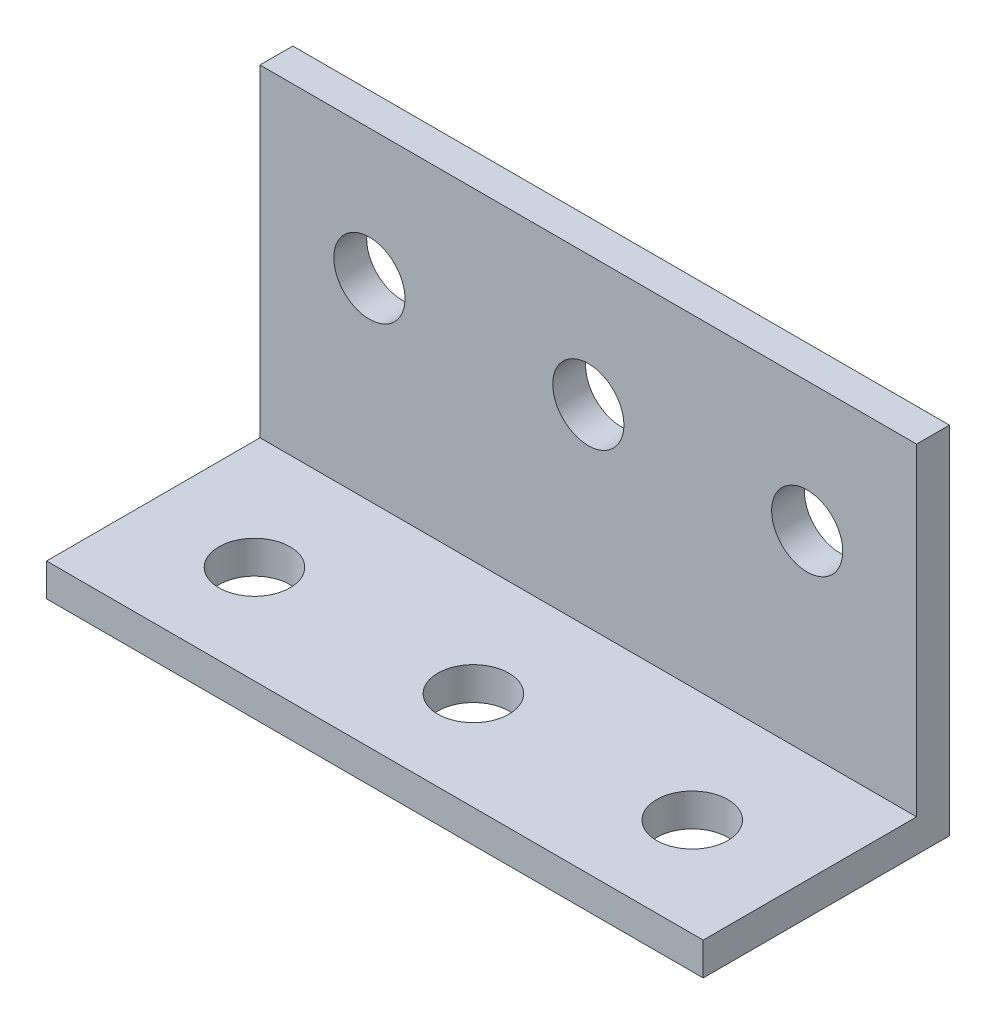
SolidWorks part; units mm, degrees
ref_plane "前视基准面" through (0, 0, 0) normal (0, 0, 1) x (1, 0, 0)
ref_plane "上视基准面" through (0, 0, 0) normal (0, 1, 0) x (1, 0, 0)
ref_plane "右视基准面" through (0, 0, 0) normal (1, 0, 0) x (0, 0, -1)
sketch "草图1" plane through (0, 0, 0) normal (0, 0, 1) x (1, 0, 0)
  line L1 (0, 0) -> (240, 0)
  line L2 (0, 0) -> (0, 130)
  line L3 (0, 130) -> (240, 130)
  line L4 (240, 0) -> (240, 130)
  dimension "D1" = 240
  dimension "D2" = 130
extrude "凸台-拉伸1" add sketch "草图1" along normal blind 90
sketch "草图2" plane through (0, 0, 0) normal (-1, 0, 0) x (0, 0, 1)
  line L0 (0, 130) -> (0, 0) construction
  line L1 (90, 130) -> (12, 130)
  line L2 (90, 130) -> (90, 12)
  line L3 (90, 12) -> (12, 12)
  line L4 (12, 130) -> (12, 12)
  line L5 (90, 0) -> (0, 0) construction
  dimension "D1" = 12
  dimension "D2" = 12
extrude "切除-拉伸1" cut sketch "草图2" against normal through all
sketch "草图3" plane through (0, 0, 0) normal (0, 0, -1) x (-1, 0, 0)
  line L0 (0, 0) -> (-240, 0) construction
  line L1 (-240, 0) -> (-240, 130) construction
  circle A0 centre (-200, 82.5) radius 13
  dimension "D1" = 26
  dimension "D2" = 82.5
  dimension "D3" = 40
extrude "切除-拉伸2" cut sketch "草图3" against normal through all
pattern_linear "阵列(线性)1" count 3 spacing 80 along (-1, 0, 0) of "切除-拉伸2"
sketch "草图4" plane through (0, 0, 0) normal (0, -1, 0) x (1, 0, 0)
  line L0 (0, 0) -> (240, 0) construction
  line L1 (0, 90) -> (0, 0) construction
  circle A0 centre (40, 54) radius 13
  dimension "D1" = 26
  dimension "D2" = 54
  dimension "D3" = 40
extrude "切除-拉伸3" cut sketch "草图4" against normal through all
pattern_linear "阵列(线性)2" count 3 spacing 80 along (1, 0, 0) of "切除-拉伸3"
